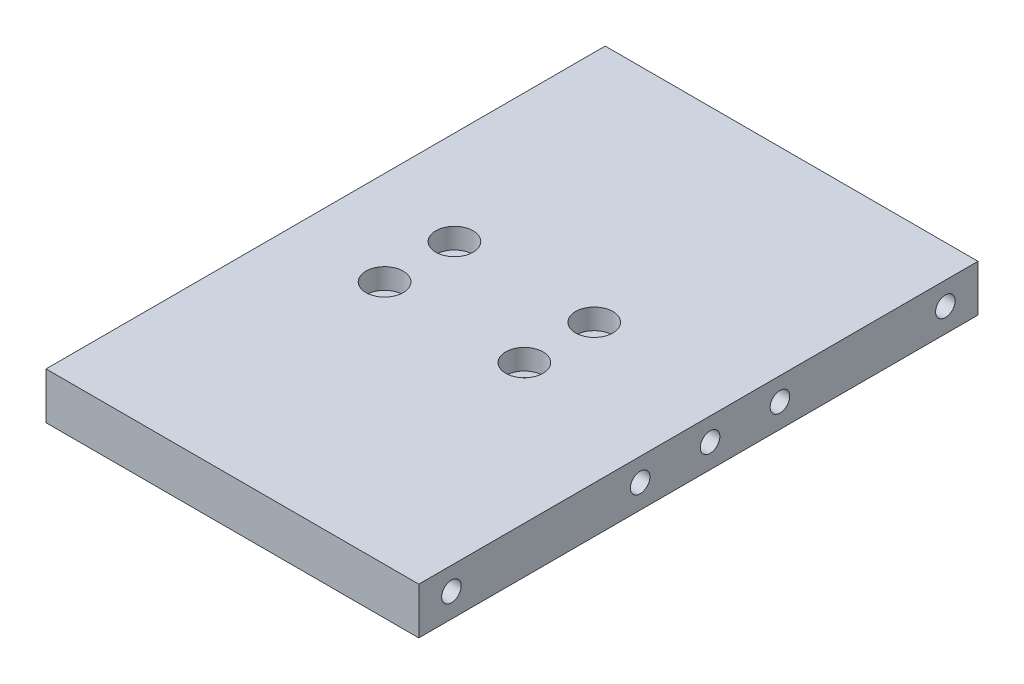
SolidWorks part; units mm, degrees
ref_plane "Ön Düzlem" through (0, 0, 0) normal (0, 0, 1) x (1, 0, 0)
ref_plane "Üst Düzlem" through (0, 0, 0) normal (0, 1, 0) x (1, 0, 0)
ref_plane "Sağ Düzlem" through (0, 0, 0) normal (1, 0, 0) x (0, 0, -1)
sketch "Sketch1" plane through (0, 0, 0) normal (0, 1, 0) x (1, 0, 0)
  line L1 (40, -60) -> (-40, -60)
  line L2 (40, -60) -> (40, 60)
  line L3 (40, 60) -> (-40, 60)
  line L4 (-40, -60) -> (-40, 60)
  line L5 (40, -60) -> (-40, 60) construction
  line L6 (40, 60) -> (-40, -60) construction
  point P0 (0, 0)
  dimension "D1" = 120
  dimension "D2" = 80
extrude "Boss-Extrude1" add sketch "Sketch1" along normal mid plane 10
hole_wizard "M5 Tapped Hole1" positions "Sketch2" profile "Sketch4" tap size "M5" standard "ISO"
sketch "Sketch2" plane through (40, 0, 17.5) normal (-1, 0, 0) x (0, 0, 1)
  point P0 (-70.5, 0.15)
  point P4 (-35, 0.15)
  point P7 (-20, 0.15)
  point P9 (-5, 0.15)
  point P44 (35.5, 0.15)
  point P60 (0, 0)
  point P61 (35.5, 0.15)
  point P63 (-5, 0.15)
  point P65 (0, 0)
  point P72 (0, 0)
  point P73 (0, 0)
  point P74 (0, 0)
  point P75 (0, 0)
  point P76 (0, 0)
  point P77 (0, 0)
sketch "Sketch4" plane through (40, 0.15, -53) normal (0, 1, 0) x (0, 0, -1)
  line L0 (0, 0) -> (0, 21.2618)
  line L1 (0, 21.2618) -> (2.1, 20)
  line L2 (2.1, 20) -> (2.1, 0)
  line L5 (2.1, 0) -> (0, 0)
  line L10 (0, 21.2618) -> (-2.1, 20) construction
  line L11 (0, -6.35) -> (0, 107.95) construction
  dimension "Tap Drill Dia." = 4.2
  dimension "Tap Drill Depth" = 20
  dimension "Drill Angle" = 118
cosmetic thread "Hole Thread6" parameters "D1"=10, "D2"=5
cosmetic thread "Hole Thread7" parameters "D1"=10, "D2"=5
cosmetic thread "Hole Thread8" parameters "D1"=10, "D2"=5
cosmetic thread "Hole Thread9" parameters "D1"=10, "D2"=5
cosmetic thread "Hole Thread10" parameters "D1"=10, "D2"=5
sketch "Sketch6" plane through (0, -5, 0) normal (0, -1, 0) x (1, 0, 0)
  line L0 (-40, -60) -> (-40, 60) construction
  line L1 (-24.85, -15) -> (15.15, -15)
  line L2 (-24.85, -15) -> (-24.85, 15)
  line L3 (-24.85, 15) -> (15.15, 15)
  line L4 (15.15, -15) -> (15.15, 15)
  line L5 (-24.85, -15) -> (15.15, 15) construction
  line L6 (-24.85, 15) -> (15.15, -15) construction
  point P0 (-4.85, 0)
  point P5 (0, 0)
  dimension "D1" = 40
  dimension "D2" = 30
  dimension "D3" = 15.15
extrude "Cut-Extrude2" cut sketch "Sketch6" against normal blind 3
hole_wizard "CBORE for M4 Hex Socket Head Cap Screw1" positions "Sketch7" profile "Sketch8" counterbore size "M4" standard "ISO"
sketch "Sketch7" plane through (0, 5, 0) normal (0, 1, 0) x (1, 0, 0)
  point P1 (-19.85, 7.5)
  point P4 (10.15, 7.5)
  point P7 (10.15, -7.5)
  point P10 (-19.85, -7.5)
  point P14 (0, 0)
  point P15 (0, 0)
  point P18 (0, 0)
  point P19 (0, 0)
sketch "Sketch8" plane through (-19.85, 5, -7.5) normal (1, 0, 0) x (0, 0, 1)
  line L0 (0, 0) -> (0, 21.3519)
  line L1 (0, 21.3519) -> (2.25, 20)
  line L2 (2.25, 20) -> (2.25, 4.4)
  line L3 (2.25, 4.4) -> (4, 4.4)
  line L4 (4, 4.4) -> (4, 0)
  line L5 (4, 0) -> (0, 0)
  line L10 (0, 21.3519) -> (-2.25, 20) construction
  line L11 (0, -6.35) -> (0, 107.95) construction
  dimension "Hole Dia." = 4.5
  dimension "Hole Depth" = 20
  dimension "C'Bore Dia." = 8
  dimension "C'Bore Depth" = 4.4
  dimension "Drill Angle" = 118
